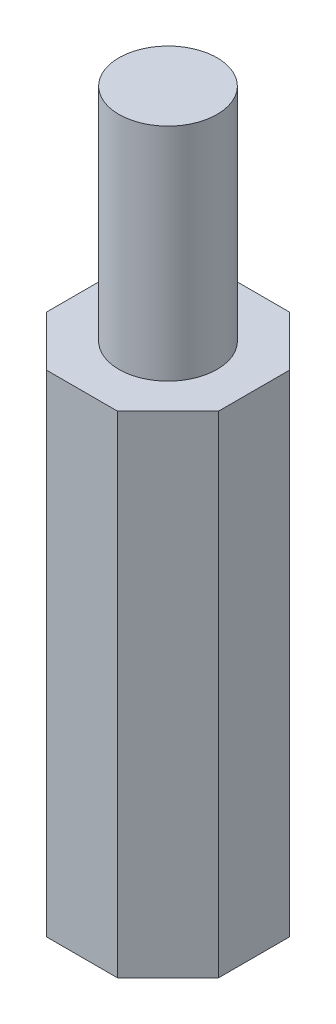
SolidWorks part; units mm, degrees
ref_plane "Plan de face" through (0, 0, 0) normal (0, 0, 1) x (1, 0, 0)
ref_plane "Plan de dessus" through (0, 0, 0) normal (0, 1, 0) x (1, 0, 0)
ref_plane "Plan de droite" through (0, 0, 0) normal (1, 0, 0) x (0, 0, -1)
sketch "Esquisse1" plane through (0, 0, 0) normal (0, 1, 0) x (1, 0, 0)
  line L0 (-1.4497, 3.5) -> (1.4497, 3.5)
  line L1 (1.4497, 3.5) -> (3.5, 1.4497)
  line L2 (3.5, 1.4497) -> (3.5, -1.4497)
  line L3 (3.5, -1.4497) -> (1.4497, -3.5)
  line L4 (1.4497, -3.5) -> (-1.4497, -3.5)
  line L5 (-1.4497, -3.5) -> (-3.5, -1.4497)
  line L6 (-3.5, -1.4497) -> (-3.5, 1.4497)
  line L7 (-3.5, 1.4497) -> (-1.4497, 3.5)
  line L8 (0, 3.5) -> (0, -3.5) construction
  dimension "D1" = 7
extrude "Extrusion1" add sketch "Esquisse1" along normal mid plane 20
sketch "Esquisse2" plane through (0, 10, 0) normal (0, 1, 0) x (1, 0, 0)
  circle A0 centre (0, 0) radius 2
  dimension "D1" = 4
extrude "Extrusion2" add sketch "Esquisse2" along normal blind 9
sketch "Esquisse3" plane through (0, -10, 0) normal (0, -1, 0) x (1, 0, 0)
  circle A0 centre (0, 0) radius 2
  dimension "D1" = 4
extrude "Enlèv. mat.-Extru.1" cut sketch "Esquisse3" against normal blind 9
